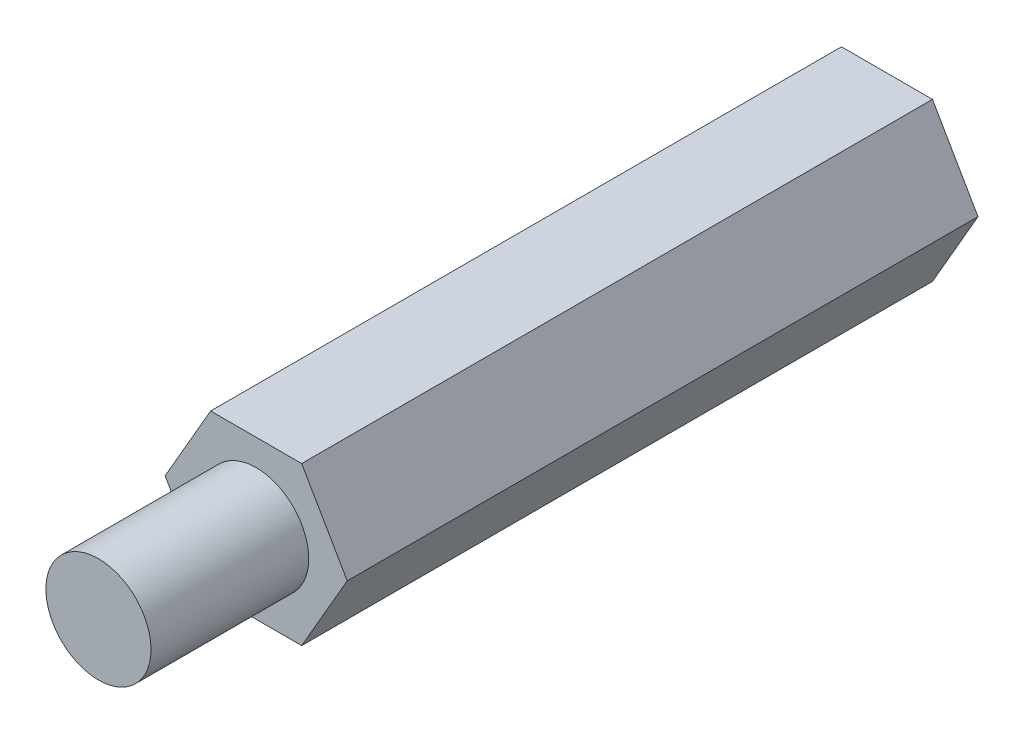
SolidWorks part; units mm, degrees
ref_plane "정면" through (0, 0, 0) normal (0, 0, 1) x (1, 0, 0)
ref_plane "윗면" through (0, 0, 0) normal (0, 1, 0) x (1, 0, 0)
ref_plane "우측면" through (0, 0, 0) normal (1, 0, 0) x (0, 0, -1)
sketch "스케치1" plane through (0, 0, 0) normal (0, 0, 1) x (1, 0, 0)
  line L1 (0.866, -1.5) -> (1.7321, 0)
  line L2 (1.7321, 0) -> (0.866, 1.5)
  line L3 (0.866, 1.5) -> (-0.866, 1.5)
  line L4 (-0.866, 1.5) -> (-1.7321, 0)
  line L5 (-1.7321, 0) -> (-0.866, -1.5)
  line L6 (-0.866, -1.5) -> (0.866, -1.5)
  circle A0 centre (0, 0) radius 1.5 construction
  dimension "D1" = 3
extrude "보스-돌출1" add sketch "스케치1" along normal blind 12
sketch "스케치2" plane through (0, 0, 12) normal (0, 0, 1) x (1, 0, 0)
  circle A0 centre (0, 0) radius 1
  dimension "D1" = 2
extrude "보스-돌출2" add sketch "스케치2" along normal blind 3
sketch "스케치3" plane through (0, 0, 0) normal (0, 0, -1) x (-1, 0, 0)
  point P0 (0, 0)
hole_wizard "M2 여유 구멍1" positions "스케치6" profile "스케치7" hole size "M2" standard "Ansi Metric"
sketch "스케치6" plane through (0, 0, 0) normal (0, 0, -1) x (-1, 0, 0)
  point P0 (0, 0)
sketch "스케치7" plane through (0, 0, 0) normal (1, 0, 0) x (0, 1, 0)
  line L0 (0, 0) -> (0, 3.721)
  line L1 (0, 3.721) -> (1.2, 3)
  line L2 (1.2, 3) -> (1.2, 0)
  line L5 (1.2, 0) -> (0, 0)
  line L10 (0, 3.721) -> (-1.2, 3) construction
  line L11 (0, -6.35) -> (0, 107.95) construction
  dimension "구멍 지름" = 2.4
  dimension "구멍 깊이" = 3
  dimension "드릴 각도" = 118
